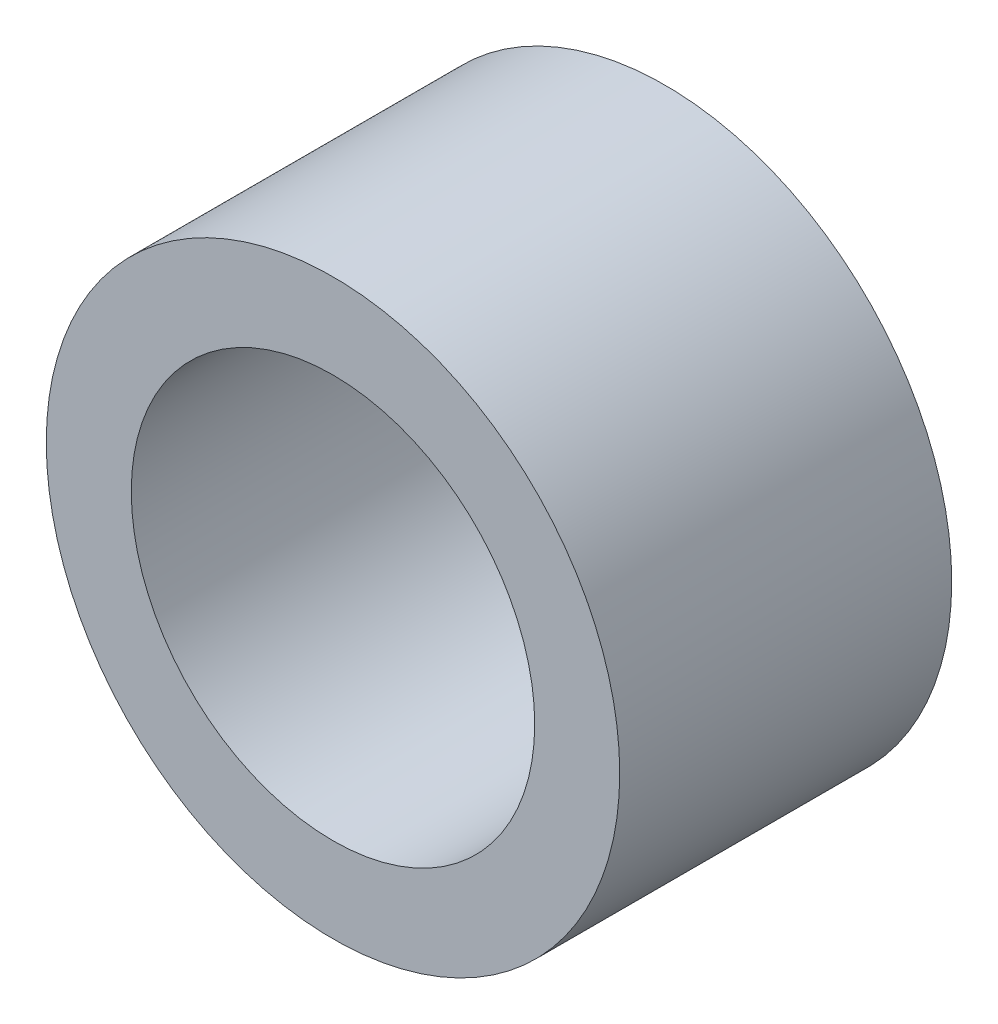
SolidWorks part; units mm, degrees
ref_plane "Front Plane" through (0, 0, 0) normal (0, 0, 1) x (1, 0, 0)
ref_plane "Top Plane" through (0, 0, 0) normal (0, 1, 0) x (1, 0, 0)
ref_plane "Right Plane" through (0, 0, 0) normal (1, 0, 0) x (0, 0, -1)
sketch "Tread annulus profile" plane through (0, 0, 0) normal (0, 0, 1) x (1, 0, 0)
  circle A0 centre (0, 0) radius 28.5
  circle A1 centre (0, 0) radius 20.05
extrude "Tread annulus" add sketch "Tread annulus profile" along normal blind 33
